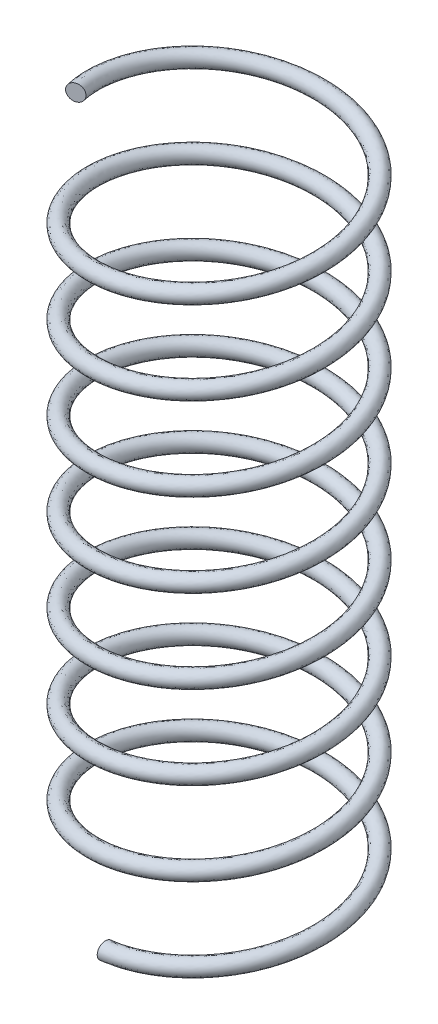
SolidWorks part; units mm, degrees
material "Alloy Steel"
ref_plane "Front Plane" through (0, 0, 0) normal (0, 0, 1) x (1, 0, 0)
ref_plane "Top Plane" through (0, 0, 0) normal (0, 1, 0) x (1, 0, 0)
ref_plane "Right Plane" through (0, 0, 0) normal (1, 0, 0) x (0, 0, -1)
sketch "Sketch1" plane through (0, 0, 0) normal (0, 1, 0) x (1, 0, 0)
  circle A0 centre (0, 0) radius 8.89
  dimension "D1" = 17.78
curve "Helix/Spiral1" pitch 6.5128 height 50.8 turns 7.8
sketch "Sketch2" plane through (0, 0, 0) normal (1, 0, 0) x (0, 0, -1)
  circle A0 centre (-8.89, 0) radius 0.635
  spline S0 degree 3 poles (-8.89, 0) (-8.89, 0.1357) (-8.421, 0.4101) (-6.4192, 0.8192) (-3.4276, 1.2291) (0.0925, 1.6387) (3.5983, 2.0484) (6.5493, 2.4581) (8.4905, 2.8677) (9.1226, 3.2774) (8.3481, 3.6871) (6.2865, 4.0968) (3.2555, 4.5065) (-0.2774, 4.9161) (-3.7675, 5.3258) (-6.6767, 5.7355) (-8.5565, 6.1452) (-9.117, 6.5548) (-8.2718, 6.9645) (-6.1511, 7.3742) (-3.0821, 7.7839) (0.4621, 8.1935) (3.9351, 8.6032) (6.8014, 9.0129) (8.619, 9.4226) (9.1076, 9.8323) (8.192, 10.2419) (6.0133, 10.6516) (2.9074, 11.0613) (-0.6467, 11.471) (-4.1012, 11.8806) (-6.9233, 12.2903) (-8.6779, 12.7) (-9.0945, 13.1097) (-8.1089, 13.5194) (-5.873, 13.929) (-2.7315, 14.3387) (0.8311, 14.7484) (4.2655, 15.1581) (7.0423, 15.5677) (8.7333, 15.9774) (9.0777, 16.3871) (8.0224, 16.7968) (5.7302, 17.2065) (2.5545, 17.6161) (-1.0151, 18.0258) (-4.4281, 18.4355) (-7.1584, 18.8452) (-8.785, 19.2548) (-9.0571, 19.6645) (-7.9327, 20.0742) (-5.5851, 20.4839) (-2.3765, 20.8935) (1.1986, 21.3032) (4.5889, 21.7129) (7.2716, 22.1226) (8.8332, 22.5323) (9.0328, 22.9419) (7.8397, 23.3516) (5.4378, 23.7613) (2.1974, 24.171) (-1.3817, 24.5806) (-4.7478, 24.9903) (-7.3819, 25.4) (-8.8777, 25.8097) (-9.0048, 26.2194) (-7.7434, 26.629) (-5.2882, 27.0387) (-2.0175, 27.4484) (1.5642, 27.8581) (4.9047, 28.2677) (7.489, 28.6774) (8.9186, 29.0871) (8.9731, 29.4968) (7.644, 29.9065) (5.1364, 30.3161) (1.8367, 30.7258) (-1.7461, 31.1355) (-5.0597, 31.5452) (-7.5931, 31.9548) (-8.9559, 32.3645) (-8.9377, 32.7742) (-7.5415, 33.1839) (-4.9825, 33.5935) (-1.6552, 34.0032) (1.9272, 34.4129) (5.2125, 34.8226) (7.6941, 35.2323) (8.9894, 35.6419) (8.8986, 36.0516) (7.4358, 36.4613) (4.8265, 36.871) (1.473, 37.2806) (-2.1076, 37.6903) (-5.3632, 38.1) (-7.7919, 38.5097) (-9.0193, 38.9194) (-8.8559, 39.329) (-7.3271, 39.7387) (-4.6686, 40.1484) (-1.2902, 40.5581) (2.2871, 40.9677) (5.5117, 41.3774) (7.8866, 41.7871) (9.0454, 42.1968) (8.8096, 42.6065) (7.2154, 43.0161) (4.5087, 43.4258) (1.1069, 43.8355) (-2.4656, 44.2452) (-5.658, 44.6548) (-7.978, 45.0645) (-9.0678, 45.4742) (-8.7596, 45.8839) (-7.1007, 46.2935) (-4.3471, 46.7032) (-0.9231, 47.1129) (2.6432, 47.5226) (5.8019, 47.9323) (8.0661, 48.3419) (9.0866, 48.7516) (8.706, 49.1613) (6.9834, 49.5709) (4.1827, 49.9808) (0.7422, 50.3899) (-1.6404, 50.6643) (-2.7472, 50.8) knots 0 0 0 0 0.008065 0.016129 0.024194 0.032258 0.040323 0.048387 0.056452 0.064516 0.072581 0.080645 0.08871 0.096774 0.104839 0.112903 0.120968 0.129032 0.137097 0.145161 0.153226 0.16129 0.169355 0.177419 0.185484 0.193548 0.201613 0.209677 0.217742 0.225806 0.233871 0.241935 0.25 0.258065 0.266129 0.274194 0.282258 0.290323 0.298387 0.306452 0.314516 0.322581 0.330645 0.33871 0.346774 0.354839 0.362903 0.370968 0.379032 0.387097 0.395161 0.403226 0.41129 0.419355 0.427419 0.435484 0.443548 0.451613 0.459677 0.467742 0.475806 0.483871 0.491935 0.5 0.508065 0.516129 0.524194 0.532258 0.540323 0.548387 0.556452 0.564516 0.572581 0.580645 0.58871 0.596774 0.604839 0.612903 0.620968 0.629032 0.637097 0.645161 0.653226 0.66129 0.669355 0.677419 0.685484 0.693548 0.701613 0.709677 0.717742 0.725806 0.733871 0.741935 0.75 0.758065 0.766129 0.774194 0.782258 0.790323 0.798387 0.806452 0.814516 0.822581 0.830645 0.83871 0.846774 0.854839 0.862903 0.870968 0.879032 0.887097 0.895161 0.903226 0.91129 0.919355 0.927419 0.935484 0.943548 0.951613 0.959677 0.967742 0.975806 0.983871 0.991935 1 1 1 1 construction
  point P4 (0, 0)
  dimension "D1" = 1.27
sweep "Sweep1" add profiles "Sketch2" path "Helix/Spiral1"
